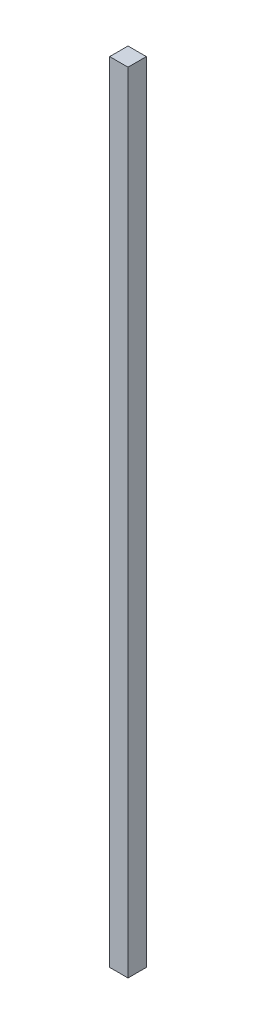
SolidWorks part; units mm, degrees
ref_plane "Front Plane" through (0, 0, 0) normal (0, 0, 1) x (1, 0, 0)
ref_plane "Top Plane" through (0, 0, 0) normal (0, 1, 0) x (1, 0, 0)
ref_plane "Right Plane" through (0, 0, 0) normal (1, 0, 0) x (0, 0, -1)
sketch "Sketch1" plane through (0, 0, 0) normal (0, 1, 0) x (1, 0, 0)
  line L1 (-10, 10) -> (10, 10)
  line L2 (-10, 10) -> (-10, -10)
  line L3 (-10, -10) -> (10, -10)
  line L4 (10, 10) -> (10, -10)
  line L5 (-10, 10) -> (10, -10) construction
  line L6 (-10, -10) -> (10, 10) construction
  point P0 (0, 0)
  dimension "D1" = 20
  dimension "D2" = 20
extrude "Boss-Extrude1" add sketch "Sketch1" along normal blind 860
